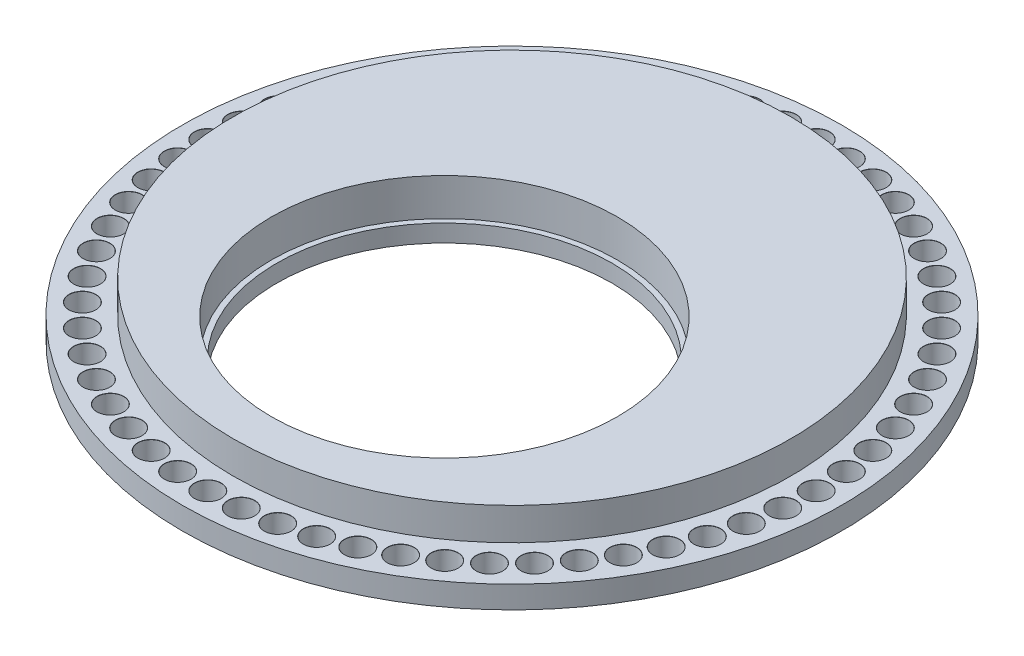
SolidWorks part; units mm, degrees
material "Custom Plastic"
ref_plane "X-Y Datum" through (0, 0, 0) normal (0, 0, 1) x (1, 0, 0)
ref_plane "X-Z Datum" through (0, 0, 0) normal (0, 1, 0) x (1, 0, 0)
ref_plane "Y-Z Datum" through (0, 0, 0) normal (1, 0, 0) x (0, 0, -1)
sketch "Sketch1" plane through (0, 0, 0) normal (0, 1, 0) x (1, 0, 0)
  line L0 (0, 0) -> (0, -12.7) construction
  line L1 (0, -43.0151) -> (0, 43.0151) construction
  line L2 (0, 52.3875) -> (0, 61.9125) construction
  circle A0 centre (0, -12.7) radius 30.988
  circle A1 centre (0, 0) radius 52.3875 construction
  circle A2 centre (0, 0) radius 61.9125
  circle A3 centre (0, 0) radius 57.15 construction
  point P12 (0, 57.15)
  dimension "D2" = 61.976
  dimension "D3" = 104.775
  dimension "D4" = 123.825
  dimension "D5" = 114.3
  dimension "D1" = 12.7
extrude "Slotted-Body Extrude" add sketch "Sketch1" along normal blind 4.191
sketch "Sketch5" plane through (0, 4.191, 0) normal (0, 1, 0) x (1, 0, 0)
  circle A0 centre (0, 0) radius 52.3875 construction
  circle A1 centre (0, 0) radius 52.3875
extrude "Boss-Extrude3" add sketch "Sketch5" along normal blind 6.08
sketch "Sketch6" plane through (0, 0, 0) normal (0, -1, 0) x (1, 0, 0)
  circle A0 centre (0, 12.7) radius 30.988 construction
  circle A1 centre (0, 12.7) radius 30.988 construction
  circle A2 centre (0, 12.7) radius 32.512
  dimension "D1" = 65.024
extrude "Cut-Extrude5" cut sketch "Sketch6" against normal through all
sketch "Sketch8" plane through (0, 0, 0) normal (0, -1, 0) x (1, 0, 0)
  circle A0 centre (0, 12.7) radius 32.512 construction
  circle A1 centre (0, 12.7) radius 32.512
  circle A2 centre (0, 12.7) radius 31.496
  dimension "D1" = 62.992
extrude "Boss-Extrude4" add sketch "Sketch8" against normal blind 3.255 separate body
hole_wizard "Ø5.0mm Dowel Hole1" positions "Sketch9" profile "Sketch10" hole size "Ø5.0" standard "ANSI Metric" end condition through all
sketch "Sketch9" plane through (0, 4.191, 0) normal (0, 1, 0) x (1, 0, 0)
  point P0 (0, 57.15)
sketch "Sketch10" plane through (0, 4.191, -57.15) normal (1, 0, 0) x (0, 0, 1)
  line L0 (0, 0) -> (0, 4.191)
  line L1 (0, 4.191) -> (2.5, 4.191)
  line L2 (2.5, 4.191) -> (2.5, 0.025)
  line L3 (2.5, 0.025) -> (2.525, 0)
  line L5 (2.525, 0) -> (0, 0)
  line L6 (-2.5, 0.025) -> (-2.525, 0) construction
  line L11 (0, -6.35) -> (0, 107.95) construction
  dimension "Thru Hole Dia." = 5
  dimension "Thru Hole Depth" = 4.191
  dimension "Near C'Sink Dia." = 5.05
  dimension "Near C'Sink Angle" = 90
pattern_circular "CirPattern1" count 60 over 360 about axis through (0, 0, 0) along (0, 1, 0) of "Ø5.0mm Dowel Hole1"
